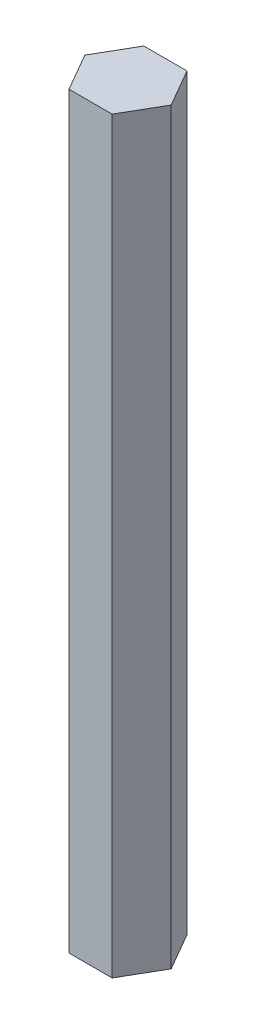
SolidWorks part; units mm, degrees
ref_plane "前视基准面" through (0, 0, 0) normal (0, 0, 1) x (1, 0, 0)
ref_plane "上视基准面" through (0, 0, 0) normal (0, 1, 0) x (1, 0, 0)
ref_plane "右视基准面" through (0, 0, 0) normal (1, 0, 0) x (0, 0, -1)
sketch "草图1" plane through (0, 0, 0) normal (0, 1, 0) x (1, 0, 0)
  line L1 (1.7321, 0) -> (0.866, 1.5)
  line L2 (0.866, 1.5) -> (-0.866, 1.5)
  line L3 (-0.866, 1.5) -> (-1.7321, 0)
  line L4 (-1.7321, 0) -> (-0.866, -1.5)
  line L5 (-0.866, -1.5) -> (0.866, -1.5)
  line L6 (0.866, -1.5) -> (1.7321, 0)
  circle A0 centre (0, 0) radius 1.5 construction
  dimension "D1" = 3
extrude "凸台-拉伸1" add sketch "草图1" along normal blind 30
